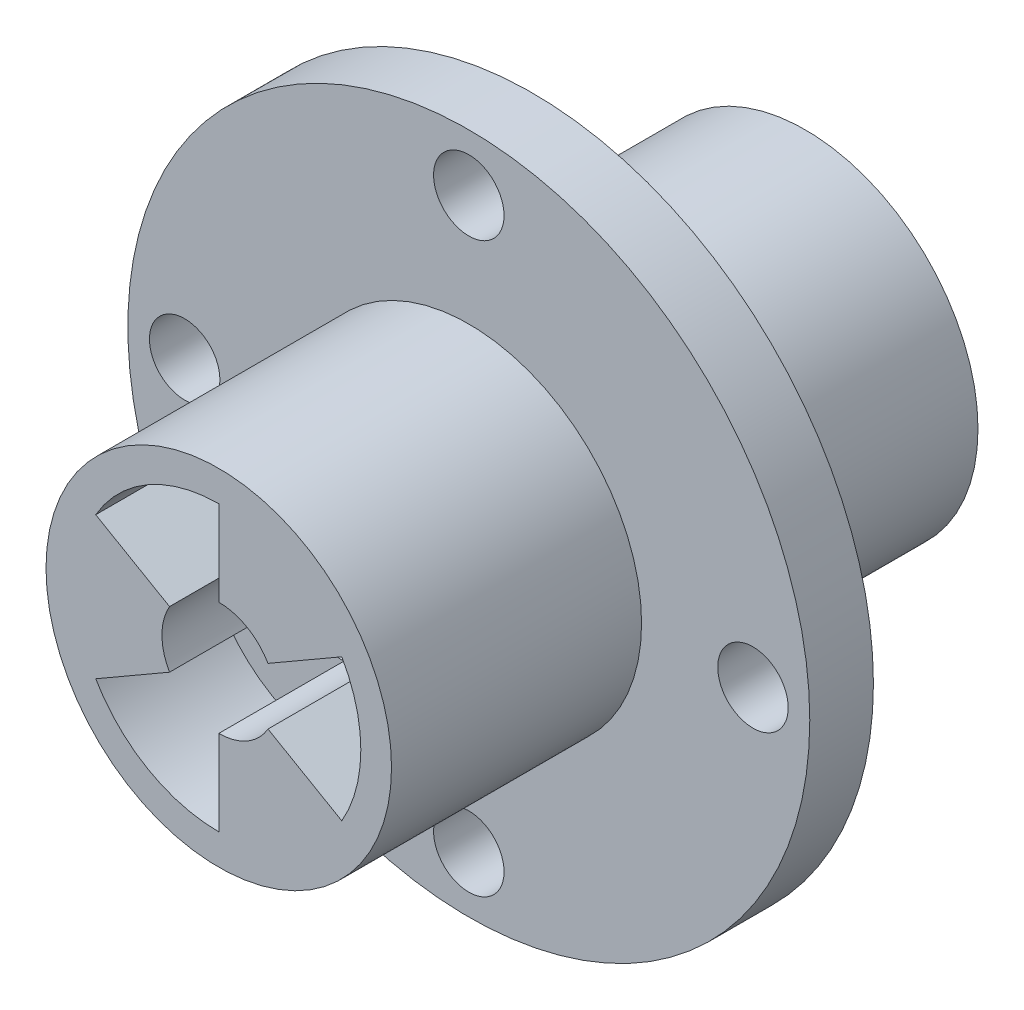
SolidWorks part; units mm, degrees
ref_plane "Front Plane" through (0, 0, 0) normal (0, 0, 1) x (1, 0, 0)
ref_plane "Top Plane" through (0, 0, 0) normal (0, 1, 0) x (1, 0, 0)
ref_plane "Right Plane" through (0, 0, 0) normal (1, 0, 0) x (0, 0, -1)
sketch "Sketch1" plane through (0, 0, 0) normal (0, 0, 1) x (1, 0, 0)
  circle A0 centre (0, 0) radius 12.5 construction
  circle A3 centre (0, 0) radius 15
  circle A4 centre (0, 12.5) radius 1.55
  circle A5 centre (12.5, 0) radius 1.55
  circle A6 centre (0, -12.5) radius 1.55
  circle A7 centre (-12.5, 0) radius 1.55
  point P15 (0, 0)
  dimension "D1" = 25
  dimension "D2" = 30
  dimension "D3" = 3.1
  dimension "D4" = 4
extrude "Boss-Extrude1" add sketch "Sketch1" along normal blind 2.8
sketch "Sketch3" plane through (0, 0, 0) normal (0, 0, 1) x (1, 0, 0)
  circle A0 centre (0, 0) radius 7.6
  dimension "D1" = 15.2
extrude "Boss-Extrude2" add sketch "Sketch3" along normal blind 11 from surface at 2.8 starting at face at (1.55, -12.5, 2.8)
sketch "Sketch4" plane through (0, 0, 13.8) normal (0, 0, 1) x (1, 0, 0)
  circle A0 centre (0, 0) radius 2.5
  dimension "D1" = 5
extrude "Cut-Extrude1" cut sketch "Sketch4" against normal through all both and the other way through all
sketch "Sketch5" plane through (0, 0, 13.8) normal (0, 0, 1) x (1, 0, 0)
  circle A0 centre (0, 0) radius 5
  dimension "D1" = 10
extrude "Cut-Extrude2" cut sketch "Sketch5" against normal blind 5.5
sketch "Sketch6" plane through (0, 0, 0) normal (0, 1, 0) x (1, 0, 0)
  line L0 (-7.6, -13.8) -> (7.6, -13.8) construction
  circle A0 centre (0, -11.3) radius 1.85
  dimension "D1" = 3.7
  dimension "D2" = 2.5
sketch "Sketch7" plane through (0, 0, 0) normal (0, 0, -1) x (-1, 0, 0)
  line L0 (1.85, 0) -> (-1.85, 0) construction
  circle A0 centre (0, 0) radius 7.6
  circle A1 centre (0, 0) radius 3.2
  dimension "D1" = 15.2
  dimension "D2" = 6.4
extrude "Boss-Extrude3" add sketch "Sketch7" along normal blind 12
sketch "Sketch8" plane through (0, 0, 0) normal (0, 0, -1) x (-1, 0, 0)
  circle A0 centre (0, 0) radius 3.2 construction
  circle A1 centre (0, 0) radius 3.2
  circle A2 centre (0, 0) radius 2.5
extrude "Boss-Extrude4" add sketch "Sketch8" along normal offset from surface (8 mm away) 4 up to face at (-7.6, 0, -12)
sketch "Sketch9" plane through (0, 0, 0) normal (0, 0, -1) x (-1, 0, 0)
  circle A0 centre (0, 0) radius 7.6 construction
  circle A1 centre (0, 0) radius 7.6
  circle A2 centre (0, 0) radius 8.25
  circle M2 centre (0, 0) radius 7.6
  dimension "D1" = 16.5
extrude "Boss-Extrude5" add sketch "Sketch9" along normal blind 3 contours A2 M2
fillet "Fillet2" radius 1 1 edges at (8.25, 0, 0)
sketch "Sketch11" plane through (0, 0, 8.3) normal (0, 0, 1) x (1, 0, 0)
  circle A1 centre (0, 0) radius 5
  circle A2 centre (0, 0) radius 5
  circle M2 centre (0, 0) radius 5
  circle M3 centre (0, 0) radius 2.5
  dimension "D1" = 0
extrude "Boss-Extrude6" add sketch "Sketch11" along normal up to surface (5.5 mm away) contours M2 M3 up to face at (5, 0, 13.8)
sketch "Sketch10" plane through (0, 0, 13.8) normal (0, 0, 1) x (1, 0, 0)
  line L0 (10.651, -6.1493) -> (-17.369, 10.028)
  line L1 (0, 12.2987) -> (0, -20.056)
  line L2 (-10.651, -6.1493) -> (17.369, 10.028)
  circle A0 centre (0, 0) radius 6.25
  point P12 (0, 0)
  circle M6 centre (0, 0) radius 2.5
  dimension "D1" = 12.5
  dimension "D2" = 3
extrude "Cut-Extrude3" cut sketch "Sketch10" against normal blind 5.5 contours L1 A0 L0 M6 | L2 A0 L1 M6 | L0 A0 L2 M6
sketch "Sketch12" plane through (0, 0, -12) normal (0, 0, -1) x (-1, 0, 0)
  circle A0 centre (0, 0) radius 2.5
extrude "Boss-Extrude7" add sketch "Sketch12" against normal offset from surface (13.3 mm away) 2 from offset 5 contours A0 up to face at (4.0819, 0, 8.3) offset against normal yes
